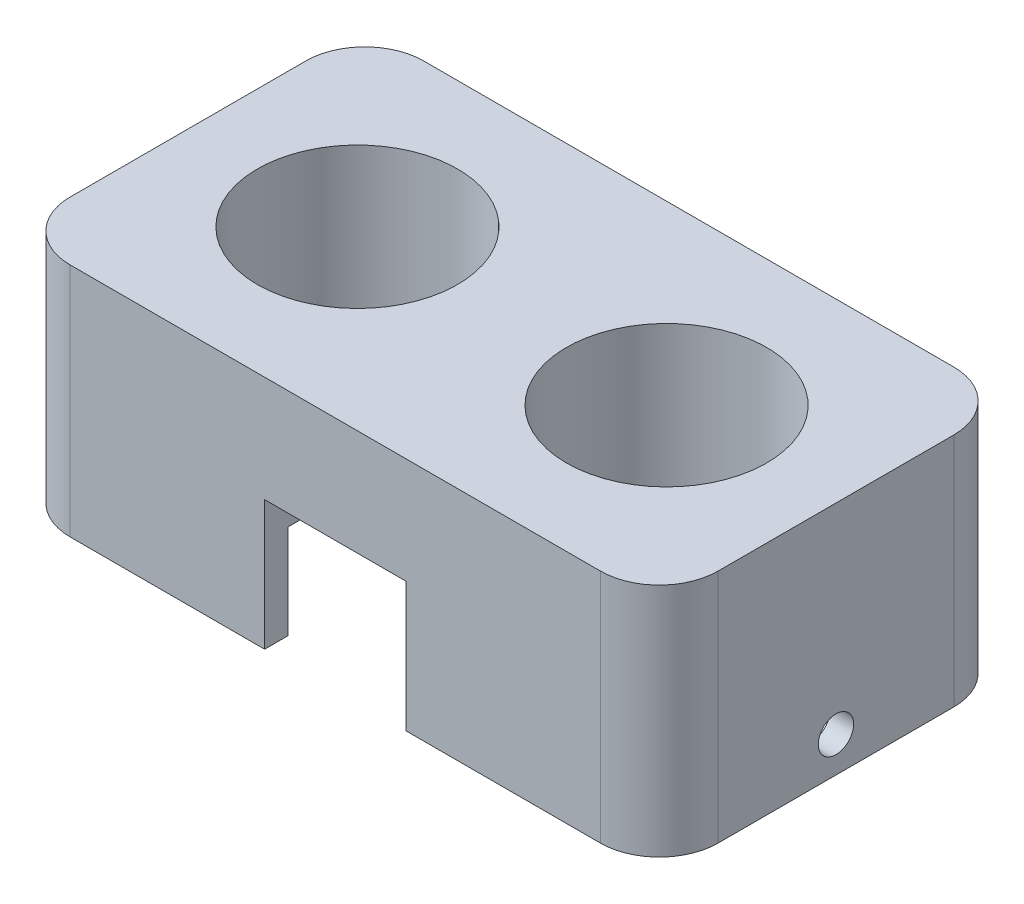
SolidWorks part; units mm, degrees
ref_plane "Front Plane" through (0, 0, 0) normal (0, 0, 1) x (1, 0, 0)
ref_plane "Top Plane" through (0, 0, 0) normal (0, 1, 0) x (1, 0, 0)
ref_plane "Right Plane" through (0, 0, 0) normal (1, 0, 0) x (0, 0, -1)
sketch "Sketch1" plane through (0, 0, 0) normal (0, 1, 0) x (1, 0, 0)
  line L1 (-27.5, -15) -> (27.5, -15)
  line L2 (-27.5, -15) -> (-27.5, 15)
  line L3 (-27.5, 15) -> (27.5, 15)
  line L4 (27.5, -15) -> (27.5, 15)
  line L5 (-27.5, -15) -> (27.5, 15) construction
  line L6 (-27.5, 15) -> (27.5, -15) construction
  point P0 (0, 0)
  dimension "D1" = 30
  dimension "D2" = 55
extrude "Boss-Extrude1" add sketch "Sketch1" along normal blind 12
sketch "Sketch2" plane through (0, 12, 0) normal (0, 1, 0) x (1, 0, 0)
  line L0 (0, 3.5755) -> (0, -2.1377) construction
  line L1 (0, 0) -> (-13.12, 0) construction
  circle A0 centre (-13.12, 0) radius 8.5
  circle A1 centre (13.12, 0) radius 8.5
  circle A2 centre (-13.12, 0) radius 10.5
  circle A3 centre (13.12, 0) radius 10.5
  dimension "D1" = 17
  dimension "D3" = 2
  dimension "D2" = 26.24
extrude "Cut-Extrude1" cut sketch "Sketch2" against normal through all contours A0 | A1
sketch "Sketch4" plane through (0, 0, 0) normal (0, -1, 0) x (1, 0, 0)
  line L0 (0, -15) -> (0, -10) construction
  line L2 (27.5, -15) -> (-27.5, -15) construction
  line L3 (6, -12.5) -> (-6, -12.5)
  line L4 (6, -12.5) -> (6, -7.5)
  line L5 (6, -7.5) -> (-6, -7.5)
  line L6 (-6, -12.5) -> (-6, -7.5)
  line L7 (6, -12.5) -> (-6, -7.5) construction
  line L8 (6, -7.5) -> (-6, -12.5) construction
  dimension "D1" = 12
  dimension "D2" = 5
  dimension "D3" = 2.5
extrude "Cut-Extrude2" cut sketch "Sketch4" against normal blind 5
fillet "Fillet1" radius 2 4 edges at (6, 2.5, -7.5) (-6, 2.5, -7.5) (-6, 2.5, -12.5) (6, 2.5, -12.5)
sketch "Sketch5" plane through (0, 0, 0) normal (0, -1, 0) x (1, 0, 0)
  line L0 (-27.5, 15) -> (27.5, 15) construction
  line L1 (-6, 10) -> (6, 10)
  line L2 (-6, 10) -> (-6, 15)
  line L3 (-6, 15) -> (6, 15)
  line L4 (6, 10) -> (6, 15)
  line L5 (-6, 10) -> (6, 15) construction
  line L6 (-6, 15) -> (6, 10) construction
  line L7 (0, 12.5) -> (0, 15) construction
  point P0 (0, 12.5)
  dimension "D1" = 12
  dimension "D2" = 5
extrude "Cut-Extrude3" cut sketch "Sketch5" against normal blind 3
fillet "Fillet2" radius 5 4 edges at (27.5, 6, 15) (-27.5, 6, -15) (27.5, 6, -15) (-27.5, 6, 15)
sketch "Sketch6" plane through (0, 0, 0) normal (0, -1, 0) x (1, 0, 0)
  line L8 (25.5, -10) -> (25.5, 10)
  line L9 (22.5, 13) -> (8, 13)
  line L13 (-8, 13) -> (-22.5, 13)
  line L14 (-25.5, 10) -> (-25.5, -10)
  line L15 (-22.5, -13) -> (22.5, -13)
  line L16 (27.5, -10) -> (27.5, 10)
  line L17 (22.5, 15) -> (6, 15)
  line L18 (6, 15) -> (6, 10)
  line L19 (6, 10) -> (-6, 10)
  line L20 (-6, 10) -> (-6, 15)
  line L21 (-6, 15) -> (-22.5, 15)
  line L22 (-27.5, 10) -> (-27.5, -10)
  line L23 (-22.5, -15) -> (22.5, -15)
  line L24 (27.5, -10) -> (27.5, 10)
  line L25 (22.5, 15) -> (6, 15)
  line L26 (6, 15) -> (6, 10)
  line L27 (6, 10) -> (-6, 10)
  line L28 (-6, 10) -> (-6, 15)
  line L29 (-6, 15) -> (-22.5, 15)
  line L30 (-27.5, 10) -> (-27.5, -10)
  line L31 (-22.5, -15) -> (22.5, -15)
  line L32 (-8, 8) -> (-8, 13) construction
  line L33 (8, 8) -> (-8, 8) construction
  line L34 (8, 13) -> (8, 8) construction
  line L35 (-8, 13) -> (-6, 13)
  line L36 (0, 16.6951) -> (0, 15.068) construction
  line L37 (8, 13) -> (6, 13)
  arc A4 (25.5, 10) -> (22.5, 13) centre (22.5, 10) ccw
  arc A5 (-22.5, 13) -> (-25.5, 10) centre (-22.5, 10) ccw
  arc A6 (-25.5, -10) -> (-22.5, -13) centre (-22.5, -10) ccw
  arc A7 (22.5, -13) -> (25.5, -10) centre (22.5, -10) ccw
  arc A8 (27.5, 10) -> (22.5, 15) centre (22.5, 10) ccw
  arc A9 (-22.5, 15) -> (-27.5, 10) centre (-22.5, 10) ccw
  arc A10 (-27.5, -10) -> (-22.5, -15) centre (-22.5, -10) ccw
  arc A11 (22.5, -15) -> (27.5, -10) centre (22.5, -10) ccw
  arc A12 (27.5, 10) -> (22.5, 15) centre (22.5, 10) ccw
  arc A13 (-22.5, 15) -> (-27.5, 10) centre (-22.5, 10) ccw
  arc A14 (-27.5, -10) -> (-22.5, -15) centre (-22.5, -10) ccw
  arc A15 (22.5, -15) -> (27.5, -10) centre (22.5, -10) ccw
  line M15 (27.5, -10) -> (27.5, 10)
  arc M16 (27.5, 10) -> (22.5, 15) centre (22.5, 10) ccw
  line M17 (22.5, 15) -> (6, 15)
  line M18 (6, 15) -> (6, 10)
  line M21 (-6, 15) -> (-22.5, 15)
  arc M22 (-22.5, 15) -> (-27.5, 10) centre (-22.5, 10) ccw
  line M23 (-27.5, 10) -> (-27.5, -10)
  arc M24 (-27.5, -10) -> (-22.5, -15) centre (-22.5, -10) ccw
  line M25 (-22.5, -15) -> (22.5, -15)
  arc M26 (22.5, -15) -> (27.5, -10) centre (22.5, -10) ccw
  dimension "D1" = 0
  dimension "D2" = 2
extrude "Boss-Extrude3" add sketch "Sketch6" along normal blind 8 contours A7 L15 A6 L14 A5 L13 L35 L28 L37 L9 A4 L8 M21 M22 M23 M24 M25 M26 M15 M16 M17 M18
hole_wizard "Ø3.0mm Dowel Hole1" positions "Sketch7" profile "Sketch9" hole size "Ø3.0" standard "ANSI Metric" end condition through all
sketch "Sketch7" plane through (-27.5, 0, 0) normal (-1, 0, 0) x (0, 0, 1)
  line L0 (0, -8) -> (0, -5) construction
  line L2 (10, -8) -> (-10, -8) construction
  point P2 (0, -5)
  dimension "D1" = 3
sketch "Sketch9" plane through (-27.5, -5, 0) normal (0, 1, 0) x (0, 0, 1)
  line L0 (0, 0) -> (0, 55)
  line L1 (0, 55) -> (1.5, 55)
  line L2 (1.5, 55) -> (1.5, 0)
  line L5 (1.5, 0) -> (0, 0)
  line L11 (0, -6.35) -> (0, 107.95) construction
  dimension "Thru Hole Dia." = 3
  dimension "Thru Hole Depth" = 55
